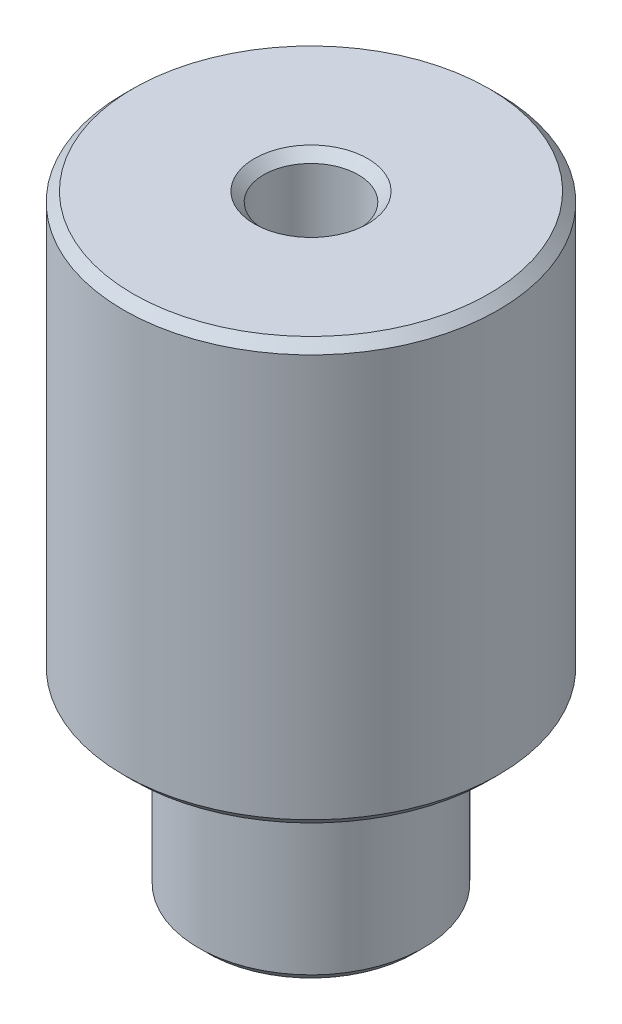
SolidWorks part; units mm, degrees
material "Plain Carbon Steel"
ref_plane "Front Plane" through (0, 0, 0) normal (0, 0, 1) x (1, 0, 0)
ref_plane "Top Plane" through (0, 0, 0) normal (0, 1, 0) x (1, 0, 0)
ref_plane "Right Plane" through (0, 0, 0) normal (1, 0, 0) x (0, 0, -1)
sketch "Sketch1" plane through (0, 0, 0) normal (0, 0, 1) x (1, 0, 0)
  line L0 (0, 0) -> (20, 0)
  line L1 (20, 0) -> (20, -45)
  line L2 (20, -45) -> (12, -45)
  line L3 (12, -45) -> (12, -65)
  line L4 (12, -65) -> (0, -65)
  line L5 (0, -65) -> (0, 0)
  line L6 (0, -70) -> (0, 5) construction
  dimension "D1" = 20
  dimension "D2" = 5
  dimension "D3" = 5
  dimension "D4" = 45
  dimension "D5" = 24
  dimension "D6" = 40
revolve "Revolve1" add sketch "Sketch1" angle 360 about L6
sketch "Sketch2" plane through (0, 0, 0) normal (0, 1, 0) x (1, 0, 0)
  circle A0 centre (0, 0) radius 5.05
  dimension "D1" = 10.1
extrude "Cut-Extrude1" cut sketch "Sketch2" against normal through all
chamfer "Chamfer1" distance 1 angle 45 5 edges at (-5.05, -65, 0) (0, -65, -12) (0, -45, -20) (-5.05, 0, 0) (0, 0, -20)
